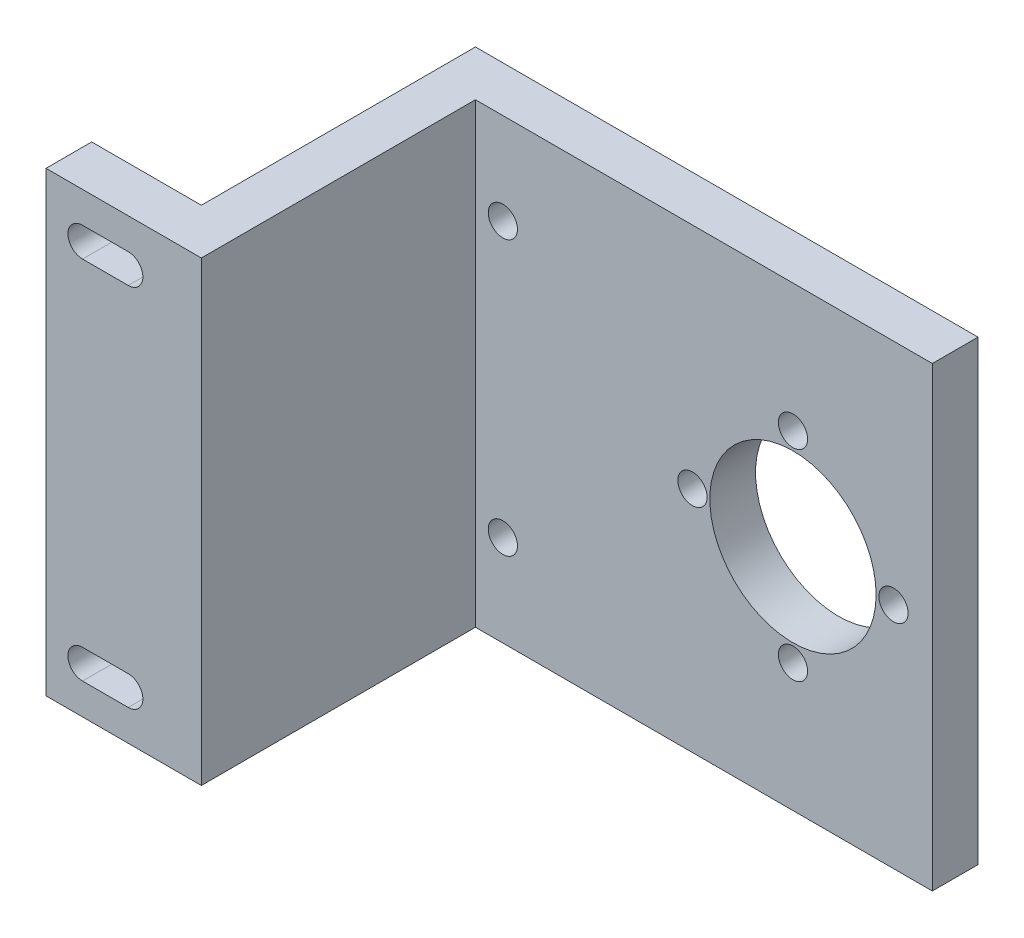
SolidWorks part; units mm, degrees
ref_plane "Front Plane" through (0, 0, 0) normal (0, 0, 1) x (1, 0, 0)
ref_plane "Top Plane" through (0, 0, 0) normal (0, 1, 0) x (1, 0, 0)
ref_plane "Right Plane" through (0, 0, 0) normal (1, 0, 0) x (0, 0, -1)
sketch "Sketch1" plane through (0, 0, 0) normal (0, 1, 0) x (1, 0, 0)
  line L0 (0, 5) -> (0, 0)
  line L1 (0, 0) -> (55, 0)
  line L3 (0, 5) -> (55, 5)
  line L4 (55, 0) -> (55, 5)
  dimension "D1" = 5
  dimension "D2" = 55
extrude "Boss-Extrude1" add sketch "Sketch1" along normal blind 50
sketch "Sketch2" plane through (0, 0, 0) normal (0, 0, 1) x (1, 0, 0)
  line L0 (39.75, 50) -> (39.75, 0) construction
  line L1 (0, 50) -> (55, 50) construction
  line L3 (0, 50) -> (0, 0) construction
  line L4 (0, 0) -> (55, 0) construction
  circle A0 centre (39.75, 25) radius 9.1
  circle A1 centre (39.75, 25) radius 11 construction
  circle A2 centre (39.75, 36) radius 1.6
  circle A3 centre (50.75, 25) radius 1.6
  circle A4 centre (39.75, 14) radius 1.6
  circle A5 centre (28.75, 25) radius 1.6
  circle A6 centre (8, 40) radius 1.6
  circle A7 centre (8, 10) radius 1.6
  point P2 (37.75, 22.5959)
  point P3 (0, 0)
  point P4 (0, 0)
  point P17 (0, 0)
  point P26 (39.75, 25)
  point P28 (0, 0)
  point P29 (37.75, 26.2021)
  point P30 (0, 0)
  dimension "D1" = 18.2
  dimension "D2" = 22
  dimension "D3" = 3.2
  dimension "D5" = 8
  dimension "D6" = 30
  dimension "D7" = 10
  dimension "D8" = 31.75
  dimension "D4" = 4
extrude "Cut-Extrude1" cut sketch "Sketch2" against normal through all
sketch "Sketch3" plane through (0, 0, 0) normal (0, 0, 1) x (1, 0, 0)
  line L0 (0, 0) -> (55, 0) construction
  line L1 (0, 50) -> (5, 50)
  line L2 (0, 50) -> (0, 0)
  line L3 (0, 0) -> (5, 0)
  line L4 (5, 50) -> (5, 0)
  dimension "D1" = 5
extrude "Boss-Extrude2" add sketch "Sketch3" along normal blind 30
sketch "Sketch4" plane through (0, 0, 30) normal (0, 0, 1) x (1, 0, 0)
  line L0 (5, 0) -> (55, 0) construction
  line L1 (5, 50) -> (-12, 50)
  line L2 (5, 50) -> (5, 0)
  line L3 (5, 0) -> (-12, 0)
  line L4 (-12, 50) -> (-12, 0)
  line L5 (-8, 45) -> (-3, 45) construction
  line L6 (-8, 46.6) -> (-3, 46.6)
  line L7 (-8, 43.4) -> (-3, 43.4)
  line L8 (-12, 25) -> (5, 25) construction
  line L9 (-8, 5) -> (-3, 5) construction
  line L10 (-8, 3.4) -> (-3, 3.4)
  line L11 (-8, 6.6) -> (-3, 6.6)
  arc A0 (-8, 46.6) -> (-8, 43.4) centre (-8, 45) ccw
  arc A1 (-3, 43.4) -> (-3, 46.6) centre (-3, 45) ccw
  arc A2 (-8, 3.4) -> (-8, 6.6) centre (-8, 5) cw
  arc A3 (-3, 6.6) -> (-3, 3.4) centre (-3, 5) cw
  point P9 (-5.5, 45)
  point P18 (-5.5, 5)
  dimension "D2" = 1.6
  dimension "D1" = 17
  dimension "D3" = 4
  dimension "D4" = 5
  dimension "D5" = 5
extrude "Boss-Extrude3" add sketch "Sketch4" against normal blind 5
